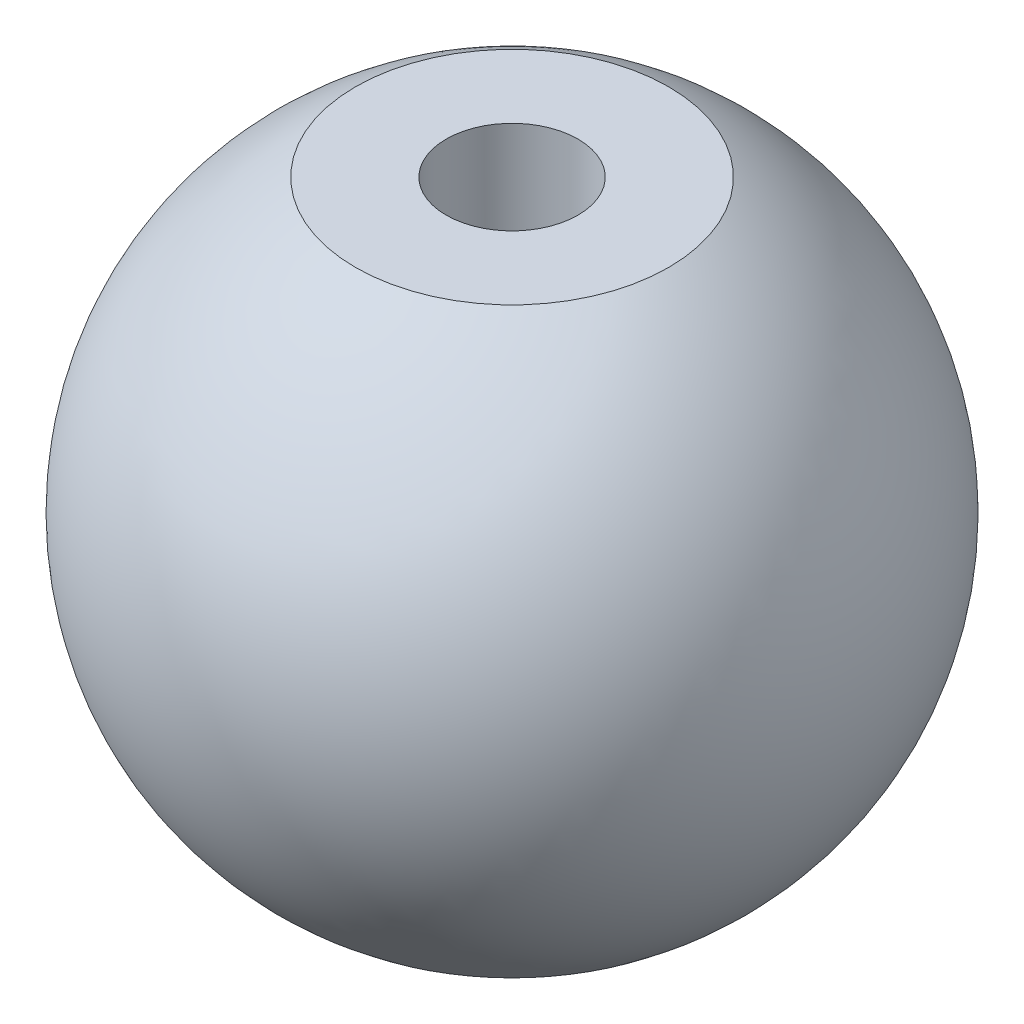
SolidWorks part; units mm, degrees
ref_plane "Plan de face" through (0, 0, 0) normal (0, 0, 1) x (1, 0, 0)
ref_plane "Plan de dessus" through (0, 0, 0) normal (0, 1, 0) x (1, 0, 0)
ref_plane "Plan de droite" through (0, 0, 0) normal (1, 0, 0) x (0, 0, -1)
sketch "Esquisse1" plane through (0, 0, 0) normal (0, 0, 1) x (1, 0, 0)
  line L0 (0, 81.3688) -> (0, -76.8483) construction
  line L1 (0, -12.5) -> (0, 12.5)
  arc A0 (0, -12.5) -> (0, 12.5) centre (0, 0) ccw
  dimension "D1" = 12.5
revolve "Révolution1" add sketch "Esquisse1" angle 360 about L0
ref_plane "Plan1" through (0, 12.5, 0) normal (0, 1, 0) x (-1, 0, 0)
hole_wizard "Trou taraudé M61" positions "Esquisse4" profile "Esquisse3" tap size "M6" standard "ISO"
sketch "Esquisse4" plane through (0, 12.5, 0) normal (0, 1, 0) x (-1, 0, 0)
  point P0 (0, 0)
sketch "Esquisse3" plane through (0, 12.5, 0) normal (1, 0, 0) x (0, 0, 1)
  line L0 (0, 0) -> (0, 21.5022)
  line L1 (0, 21.5022) -> (2.5, 20)
  line L2 (2.5, 20) -> (2.5, 0)
  line L5 (2.5, 0) -> (0, 0)
  line L10 (0, 21.5022) -> (-2.5, 20) construction
  line L11 (0, -6.35) -> (0, 107.95) construction
  dimension "Diamètre du trou pour taraudage" = 5
  dimension "Profondeur du trou pour taraudage" = 20
  dimension "Angle de pointe" = 118
cosmetic thread "Filetage de perçage1" parameters "D1"=15, "D2"=6
sketch "Esquisse5" plane through (0, 0, 0) normal (0, 0, 1) x (1, 0, 0)
  line L0 (13.75, 12.5) -> (-13.75, 12.5) construction
  line L1 (-5.9372, 11) -> (5.9372, 11)
  line L2 (-5.9372, 11) -> (-5.9372, 14.7863)
  line L3 (-5.9372, 14.7863) -> (5.9372, 14.7863)
  line L4 (5.9372, 11) -> (5.9372, 14.7863)
  arc A0 (-2.5, 12.2474) -> (2.5, 12.2474) centre (0, 0) ccw construction
  dimension "D1" = 1.5
extrude "Extrusion1" cut sketch "Esquisse5" against normal through all and the other way through all
